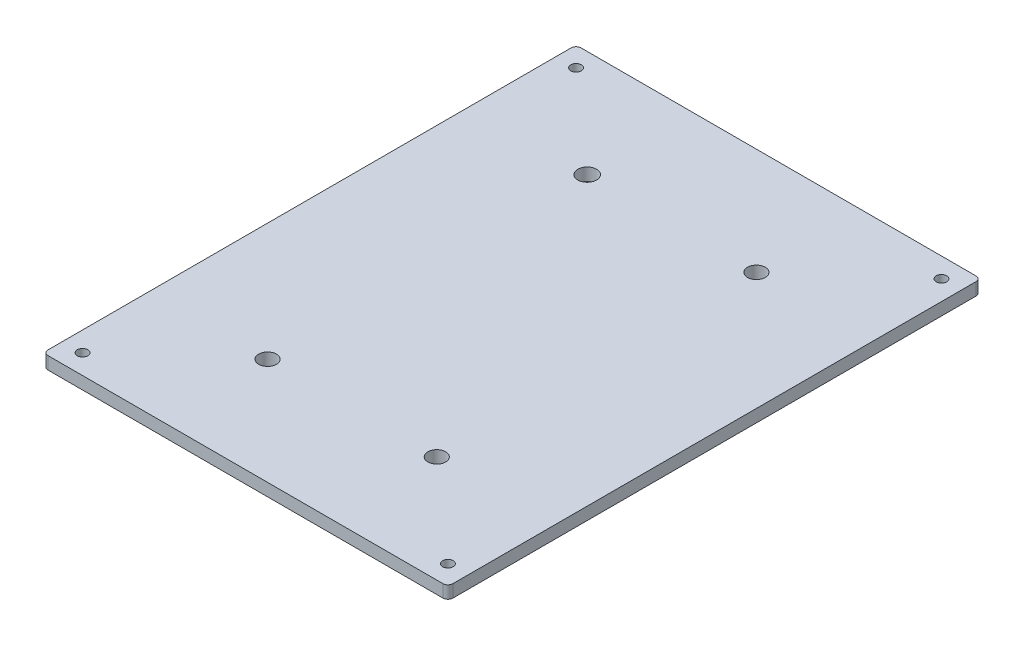
SolidWorks part; units mm, degrees
ref_plane "Front Plane" through (0, 0, 0) normal (0, 0, 1) x (1, 0, 0)
ref_plane "Top Plane" through (0, 0, 0) normal (0, 1, 0) x (1, 0, 0)
ref_plane "Right Plane" through (0, 0, 0) normal (1, 0, 0) x (0, 0, -1)
sketch "Sketch1" plane through (0, 0, 0) normal (0, 1, 0) x (1, 0, 0)
  line L1 (102.55, 135) -> (-102.55, 135)
  line L2 (102.55, 135) -> (102.55, -135)
  line L3 (102.55, -135) -> (-102.55, -135)
  line L4 (-102.55, 135) -> (-102.55, -135)
  line L5 (102.55, 135) -> (-102.55, -135) construction
  line L6 (102.55, -135) -> (-102.55, 135) construction
  point P0 (0, 0)
  dimension "D1" = 270
  dimension "D2" = 205.1
extrude "Boss-Extrude1" add sketch "Sketch1" along normal blind 6.35
fillet "Fillet1" radius 2.54 4 edges at (-102.55, 3.175, -135) (102.55, 3.175, -135) (102.55, 3.175, 135) (-102.55, 3.175, 135)
sketch "Sketch2" plane through (0, 6.35, 0) normal (0, 1, 0) x (1, 0, 0)
  line L0 (100.01, 135) -> (-100.01, 135) construction
  line L1 (-42.8625, 80.9625) -> (42.8625, 80.9625) construction
  line L2 (-42.8625, 80.9625) -> (-42.8625, -80.9625) construction
  line L3 (-42.8625, -80.9625) -> (42.8625, -80.9625) construction
  line L4 (42.8625, 80.9625) -> (42.8625, -80.9625) construction
  line L5 (-42.8625, 80.9625) -> (42.8625, -80.9625) construction
  line L6 (-42.8625, -80.9625) -> (42.8625, 80.9625) construction
  line L7 (0, 135) -> (0, 80.9625) construction
  line L8 (0, 80.9625) -> (0, -80.9625) construction
  line L9 (0, -80.9625) -> (0, -135) construction
  line L10 (-100.01, -135) -> (100.01, -135) construction
  line L11 (42.8625, 0) -> (102.55, 0) construction
  line L12 (102.55, -132.46) -> (102.55, 132.46) construction
  line L13 (-42.8625, 0) -> (-102.55, 0) construction
  line L14 (-102.55, 132.46) -> (-102.55, -132.46) construction
  circle A0 centre (-42.8625, 80.9625) radius 4.7625
  circle A1 centre (-42.8625, -80.9625) radius 4.5
  circle A2 centre (42.8625, -80.9625) radius 4.5
  circle A4 centre (42.8625, 80.9625) radius 4.5
  point P5 (0, 0)
  dimension "D4" = 9.525
  dimension "D2" = 85.725
  dimension "D3" = 161.925
sketch "Sketch3" plane through (0, 6.35, 0) normal (0, 1, 0) x (-1, 0, 0)
  line L0 (92.55, -135) -> (92.55, 135) construction
  line L1 (-100.01, -135) -> (100.01, -135) construction
  line L2 (100.01, 135) -> (-100.01, 135) construction
  line L3 (102.55, 125) -> (-102.55, 125) construction
  line L4 (102.55, -132.46) -> (102.55, 132.46) construction
  line L5 (-102.55, 132.46) -> (-102.55, -132.46) construction
  line L6 (-92.55, -135) -> (-92.55, 135) construction
  circle A0 centre (92.55, 125) radius 2.665
  circle A1 centre (-92.55, 125) radius 2.665
  circle A2 centre (-92.55, -125) radius 2.665
  circle A3 centre (92.55, -125) radius 2.665
  dimension "D4" = 10
  dimension "D5" = 10
  dimension "D6" = 5.33
  dimension "D1" = 10
  dimension "D2" = 10
  dimension "D3" = 10
extrude "Cut-Extrude2" cut sketch "Sketch3" against normal up to next
extrude "Cut-Extrude3" cut sketch "Sketch2" against normal up to next
